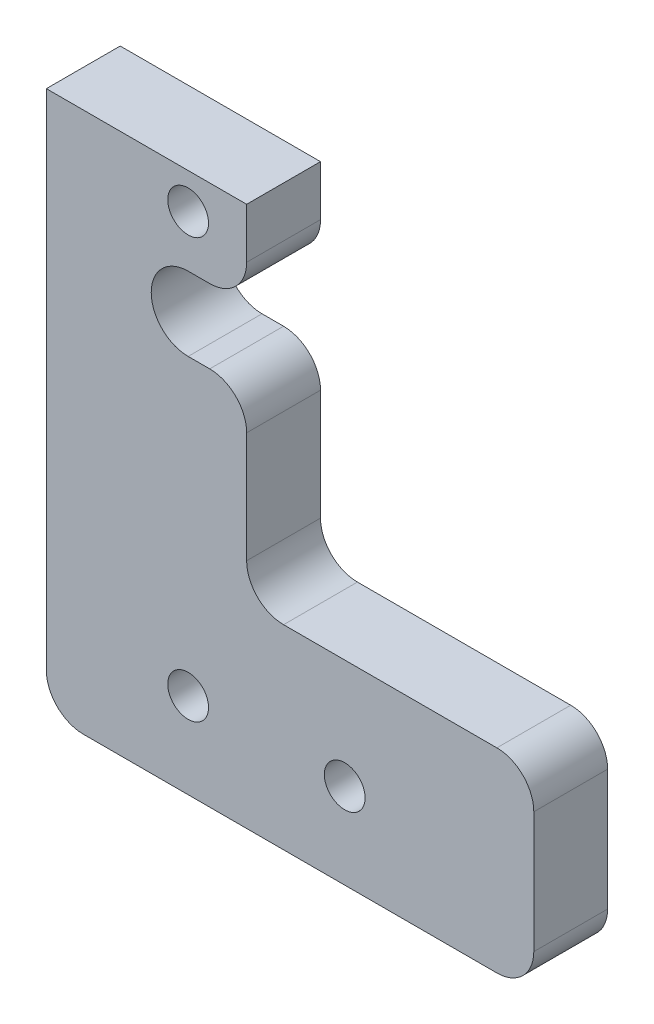
SolidWorks part; units mm, degrees
ref_plane "Front Plane" through (0, 0, 0) normal (0, 0, 1) x (1, 0, 0)
ref_plane "Top Plane" through (0, 0, 0) normal (0, 1, 0) x (1, 0, 0)
ref_plane "Right Plane" through (0, 0, 0) normal (1, 0, 0) x (0, 0, -1)
sketch "Sketch1" plane through (0, 0, 0) normal (0, 0, 1) x (1, 0, 0)
  line L0 (-17.2212, 29.718) -> (-17.2212, -13.589)
  line L1 (-14.0462, -16.764) -> (21.5138, -16.764)
  line L2 (24.6888, -13.589) -> (24.6888, -3.175)
  line L3 (21.5138, 0) -> (3.175, 0)
  line L4 (0, 3.175) -> (0, 29.718)
  line L6 (0, 29.718) -> (-17.2212, 29.718)
  line L7 (-5.0292, -9.398) -> (8.4328, -9.398) construction
  circle A0 centre (-5.0292, 26.67) radius 1.7526
  arc A1 (0, 3.175) -> (3.175, 0) centre (3.175, 3.175) ccw
  arc A2 (24.6888, -3.175) -> (21.5138, 0) centre (21.5138, -3.175) ccw
  arc A3 (24.6888, -13.589) -> (21.5138, -16.764) centre (21.5138, -13.589) cw
  arc A4 (-14.0462, -16.764) -> (-17.2212, -13.589) centre (-14.0462, -13.589) cw
  circle A5 centre (-5.0292, -9.398) radius 1.7526
  circle A6 centre (8.4328, -9.398) radius 1.7526
  point P14 (0, 0)
  point P17 (24.6888, 0)
  point P20 (24.6888, -16.764)
  point P23 (-17.2212, -16.764)
  point P26 (-17.2212, 29.718)
  dimension "D5" = 12.192
  dimension "D7" = 3.175
  dimension "D11" = 3.5052
  dimension "D6" = 43.434
  dimension "D1" = 41.91
  dimension "D2" = 46.482
  dimension "D3" = 16.764
  dimension "D4" = 17.2212
  dimension "D8" = 7.366
  dimension "D9" = 16.256
  dimension "D10" = 13.462
extrude "Boss-Extrude1" add sketch "Sketch1" along normal mid plane 6.35
sketch "Sketch2" plane through (0, 0, 3.175) normal (0, 0, 1) x (1, 0, 0)
  line L0 (-14.0462, -16.764) -> (21.5138, -16.764) construction
  line L1 (-5.0292, 22.225) -> (24.6888, 22.225)
  line L2 (24.6888, 22.225) -> (24.6888, 15.875)
  line L3 (24.6888, 15.875) -> (-5.0292, 15.875)
  line L4 (24.6888, -13.589) -> (24.6888, -3.175) construction
  line L5 (-17.2212, 29.718) -> (-17.2212, -13.589) construction
  circle A0 centre (-5.0292, 19.05) radius 3.175 construction
  arc A1 (-5.0292, 15.875) -> (-5.0292, 22.225) centre (-5.0292, 19.05) cw
  dimension "D2" = 6.35
  dimension "D1" = 35.814
  dimension "D3" = 12.192
extrude "Cut-Extrude1" cut sketch "Sketch2" against normal through all
fillet "Fillet1" radius 3.175 2 edges at (0, 22.225, 0) (0, 15.875, 0)
